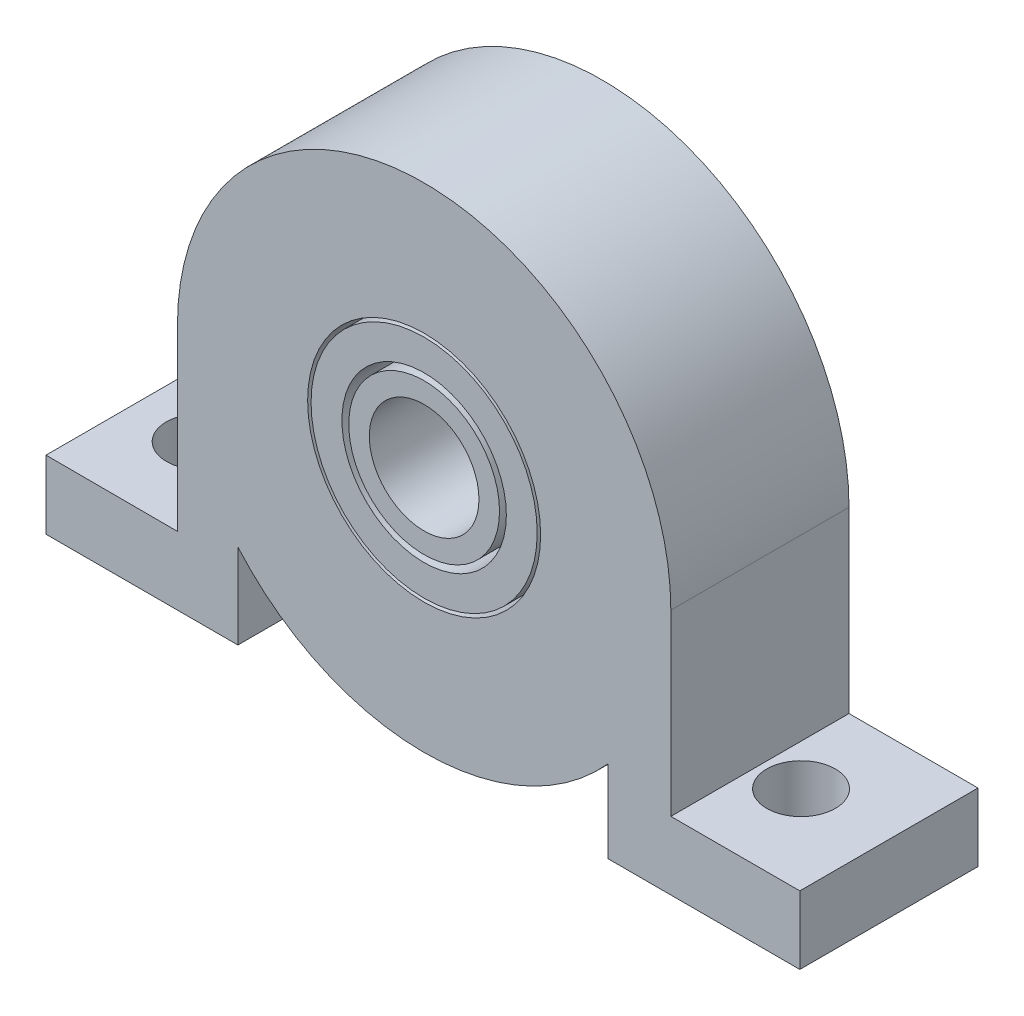
SolidWorks part; units mm, degrees
ref_plane "Front Plane" through (0, 0, 0) normal (0, 0, 1) x (1, 0, 0)
ref_plane "Top Plane" through (0, 0, 0) normal (0, 1, 0) x (1, 0, 0)
ref_plane "Right Plane" through (0, 0, 0) normal (1, 0, 0) x (0, 0, -1)
sketch "Sketch1" plane through (0, 0, 0) normal (0, 0, 1) x (1, 0, 0)
  line L0 (0, -2.4919) -> (0, 15.5081) construction
  line L1 (27.4108, -2.4919) -> (13.4108, -2.4919)
  line L2 (27.4108, -2.4919) -> (27.4108, 2.4758)
  line L3 (27.4108, 2.4758) -> (18, 2.4758)
  line L4 (-27.5892, -2.4919) -> (-27.5892, 2.5081)
  line L5 (27.4108, -2.4919) -> (-13.5892, 1.2354) construction
  line L6 (13.4108, 1.2113) -> (-7.8168, -0.706) construction
  line L7 (-18, 15.5081) -> (-18, 2.4758)
  line L8 (18, 15.5081) -> (18, 2.4758)
  line L13 (-13.5892, -2.4919) -> (-27.5892, -2.4919)
  line L14 (-13.0345, -1.1773) -> (-27.5892, -2.4919) construction
  line L15 (-13.5892, 3.7041) -> (-13.5892, -2.4919)
  line L16 (-18, 2.486) -> (-27.5892, 2.5081)
  line L17 (13.4108, -2.4919) -> (13.4108, 3.5019)
  arc A1 (-13.5892, 3.7041) -> (13.4108, 3.5019) centre (0, 15.5081) ccw
  arc A5 (18, 15.5081) -> (-18, 15.5081) centre (0, 15.5081) ccw
  point P0 (0, 0)
  dimension "D1" = 55
  dimension "D2" = 5
  dimension "D3" = 18
  dimension "D7" = 14
extrude "Boss-Extrude1" add sketch "Sketch1" along normal blind 13
sketch "Sketch2" plane through (0, 0, 13) normal (0, 0, 1) x (1, 0, 0)
  line L0 (0, 0) -> (0, 31.0162) construction
  line L1 (27.4108, -2.4919) -> (13.4108, -2.4919) construction
  circle A0 centre (0, 15.5081) radius 4
  dimension "D1" = 8
  dimension "D2" = 18
extrude "Cut-Extrude1" cut sketch "Sketch2" against normal through all
sketch "Sketch3" plane through (0, 0, 13) normal (0, 0, 1) x (1, 0, 0)
  circle A0 centre (0, 15.5081) radius 5.5
  circle A1 centre (0, 15.5081) radius 6
  dimension "D1" = 11
  dimension "D2" = 12
extrude "Cut-Extrude3" cut sketch "Sketch3" against normal through all
sketch "Sketch4" plane through (0, 0, 13) normal (0, 0, 1) x (1, 0, 0)
  circle A0 centre (0, 15.5081) radius 8
  circle A1 centre (0, 15.5081) radius 8.25
  circle A2 centre (0, 15.5081) radius 8.5
  circle A3 centre (0, 15.5081) radius 9
  dimension "D1" = 16
  dimension "D2" = 16.5
  dimension "D3" = 17
  dimension "D4" = 18
extrude "Cut-Extrude4" cut sketch "Sketch4" against normal through all contours A1 | A2
sketch "Sketch5" plane through (0, 2.4758, 0) normal (0, 1, 0) x (1, 0, 0)
  line L1 (0, 0) -> (0, -13) construction
  line L2 (18, 0) -> (-18, 0) construction
  line L3 (-18, -13) -> (18, -13) construction
  circle A0 centre (21, -6.5) radius 2.5
  circle A1 centre (-21, -6.5) radius 2.5
  dimension "D1" = 21
  dimension "D4" = 5
  dimension "D2" = 21
extrude "Cut-Extrude5" cut sketch "Sketch5" against normal blind 13 contours A0 | A1
sketch "Sketch6" plane through (0.0056, 2.4444, 0) normal (0.0023, 1, 0) x (1, -0.0023, 0)
  circle A0 centre (-22.8154, -6.5) radius 2.5
  dimension "D1" = 5
extrude "Cut-Extrude6" cut sketch "Sketch6" against normal blind 13
sketch "Sketch7" plane through (0, 0, 13) normal (0, 0, 1) x (1, 0, 0)
